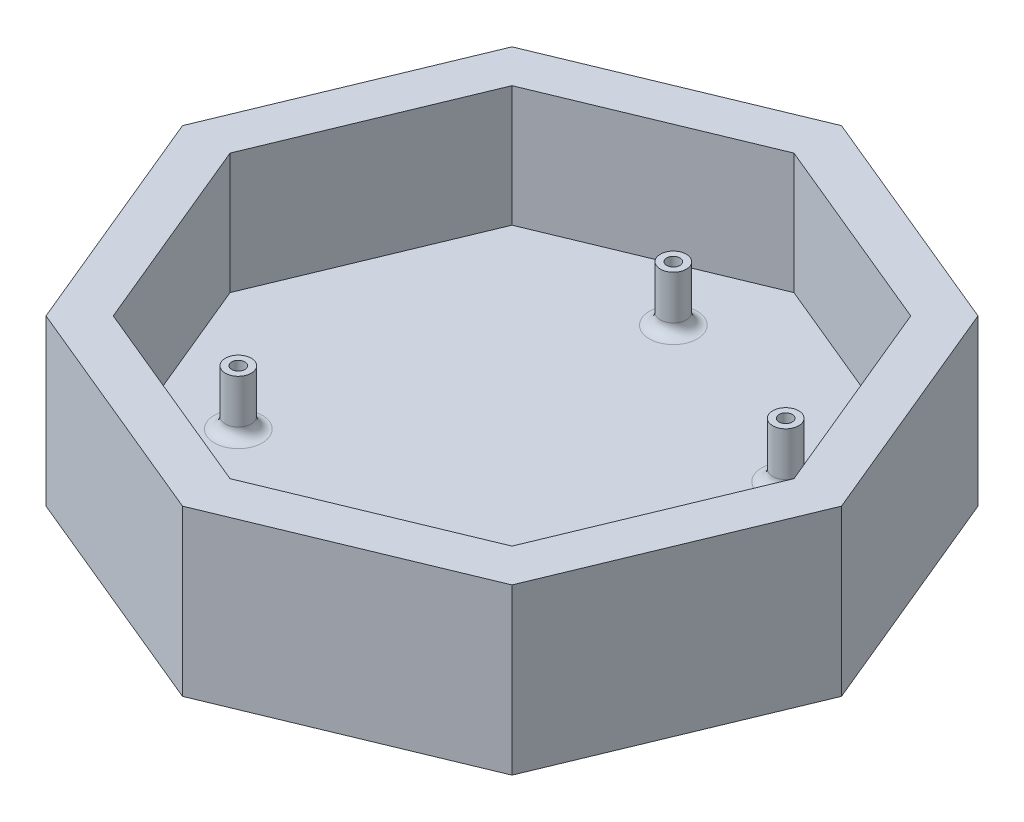
SolidWorks part; units mm, degrees
ref_plane "Front Plane" through (0, 0, 0) normal (0, 0, 1) x (1, 0, 0)
ref_plane "Top Plane" through (0, 0, 0) normal (0, 1, 0) x (1, 0, 0)
ref_plane "Right Plane" through (0, 0, 0) normal (1, 0, 0) x (0, 0, -1)
sketch "Sketch1" plane through (0, 0, 0) normal (0, 1, 0) x (1, 0, 0)
  line L1 (76.2, 0) -> (53.8815, 53.8815)
  line L2 (53.8815, 53.8815) -> (0, 76.2)
  line L3 (0, 76.2) -> (-53.8815, 53.8815)
  line L4 (-53.8815, 53.8815) -> (-76.2, 0)
  line L5 (-76.2, 0) -> (-53.8815, -53.8815)
  line L6 (-53.8815, -53.8815) -> (0, -76.2)
  line L7 (0, -76.2) -> (53.8815, -53.8815)
  line L8 (53.8815, -53.8815) -> (76.2, 0)
  circle A0 centre (0, 0) radius 70.3996 construction
  dimension "D1" = 152.4
extrude "Boss-Extrude1" add sketch "Sketch1" along normal blind 38.1 contours L4 L5 L6 L7 L8 L1 L2 L3
shell "Shell1" thickness 10.16
sketch "Sketch5" plane through (0, 10.16, 0) normal (0, 1, 0) x (1, 0, 0)
  line L0 (23.0527, 55.6542) -> (-23.0527, -55.6542) construction
  line L1 (46.1054, 46.1054) -> (0, 65.2029) construction
  line L2 (-46.1054, -46.1054) -> (0, -65.2029) construction
  line L3 (-55.6542, 23.0527) -> (55.6542, -23.0527) construction
  line L4 (-46.1054, 46.1054) -> (-65.2029, 0) construction
  line L5 (46.1054, -46.1054) -> (65.2029, 0) construction
  circle A0 centre (-7.4398, 44.7538) radius 3.0007
  circle A1 centre (36.9064, 26.385) radius 3.0007
  circle A2 centre (7.4398, -44.7538) radius 3.0007
  circle A3 centre (-36.9064, -26.385) radius 3.0007
  point P14 (36.9064, 26.385)
  point P17 (-36.9064, -26.385)
  point P18 (7.4398, -44.7538)
  dimension "D1" = 24
  dimension "D2" = 38.5
extrude "Boss-Extrude2" add sketch "Sketch5" along normal blind 12.7
fillet "Fillet2" radius 2.54 4 edges at (7.4398, 10.16, 47.7544) (-36.9064, 10.16, 23.3843) (36.9064, 10.16, -29.3856) (-7.4398, 10.16, -41.7531)
hole_wizard "Tap Drill for #4 Helicoil2" positions "Sketch8" profile "Sketch9" hole size "#4-40" standard "ANSI Inch"
sketch "Sketch8" plane through (0, 22.86, 0) normal (0, 1, 0) x (1, 0, 0)
  point P0 (-7.4398, 44.7538)
  point P3 (36.9064, 26.385)
  point P6 (7.4398, -44.7538)
  point P9 (-36.9064, -26.385)
sketch "Sketch9" plane through (-7.4398, 22.86, -44.7538) normal (1, 0, 0) x (0, 0, 1)
  line L0 (0, 0) -> (0, 9.8057)
  line L1 (0, 9.8057) -> (1.524, 8.89)
  line L2 (1.524, 8.89) -> (1.524, 0)
  line L5 (1.524, 0) -> (0, 0)
  line L10 (0, 9.8057) -> (-1.524, 8.89) construction
  line L11 (0, -6.35) -> (0, 107.95) construction
  dimension "Hole Dia." = 3.048
  dimension "Hole Depth" = 8.89
  dimension "Drill Angle" = 118
